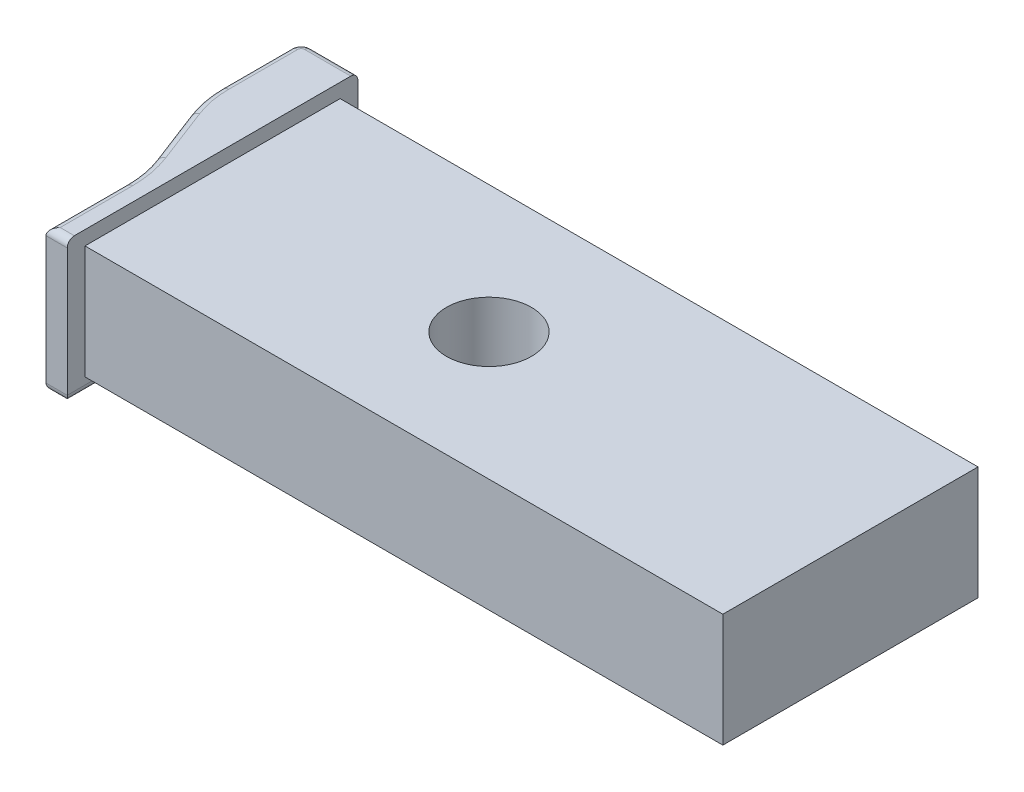
SolidWorks part; units mm, degrees
ref_plane "Спереди" through (0, 0, 0) normal (0, 0, 1) x (1, 0, 0)
ref_plane "Сверху" through (0, 0, 0) normal (0, 1, 0) x (1, 0, 0)
ref_plane "Справа" through (0, 0, 0) normal (1, 0, 0) x (0, 0, -1)
sketch "Эскиз1" plane through (0, 0, 0) normal (0, 1, 0) x (1, 0, 0)
  line L1 (-45, 18) -> (45, 18)
  line L2 (-45, 18) -> (-45, -18)
  line L3 (-45, -18) -> (45, -18)
  line L4 (45, 18) -> (45, -18)
  line L5 (-45, 18) -> (45, -18) construction
  line L6 (-45, -18) -> (45, 18) construction
  circle A0 centre (-6, 0) radius 6
  point P0 (0, 0)
  dimension "D3" = 12
  dimension "D1" = 90
  dimension "D2" = 36
  dimension "D4" = 51
extrude "Бобышка-Вытянуть1" add sketch "Эскиз1" along normal blind 16
ref_plane "Плоскость2" through (0, 18, 0) normal (0, 1, 0) x (1, 0, 0)
sketch "Эскиз3" plane through (0, 18, 0) normal (0, 1, 0) x (1, 0, 0)
  line L0 (-45, 20.5) -> (-45, -20.5)
  line L2 (-45, 18) -> (-45, -18) construction
  line L3 (-45, -20.5) -> (-48, -20.5)
  line L4 (-45, 20.5) -> (-51.5, 20.5)
  line L5 (-53, 19) -> (-53, 9.2852)
  line L6 (-48, -20.5) -> (-48, -9.2852)
  line L7 (-52.0002, 3.9005) -> (-48.9998, -3.9005)
  arc A0 (-52.0002, 3.9005) -> (-53, 9.2852) centre (-38, 9.2852) cw
  arc A1 (-48, -9.2852) -> (-48.9998, -3.9005) centre (-63, -9.2852) ccw
  arc A2 (-53, 19) -> (-51.5, 20.5) centre (-51.5, 19) cw
  point P2 (-45, 0)
  point P5 (-45, 0)
  point P14 (-53, 6.5)
  point P17 (-48, -6.5)
  point P20 (-53, 20.5)
  dimension "D6" = 15
  dimension "D7" = 15
  dimension "D8" = 1.5
  dimension "D1" = 41
  dimension "D2" = 3
  dimension "D3" = 8
  dimension "D4" = 14
  dimension "D5" = 14
extrude "Бобышка-Вытянуть2" add sketch "Эскиз3" against normal blind 20
fillet "Скругление1" radius 1 8 edges at (-46.5, 18, 20.5) (-48, 18, 14.8926) (-48.2521, 18, 6.5468) (-50.5, 18, 0) (-52.7479, 18, -6.5468) (-53, 18, -14.1426) (-52.5607, 18, -20.0607) (-48.25, 18, -20.5)
fillet "Скругление2" radius 1 9 edges at (-45, -2, 0) (-46.5, -2, 20.5) (-48, -2, 14.8926) (-48.2521, -2, 6.5468) (-50.5, -2, 0) (-52.7479, -2, -6.5468) (-53, -2, -14.1426) (-52.5607, -2, -20.0607) (-48.25, -2, -20.5)
